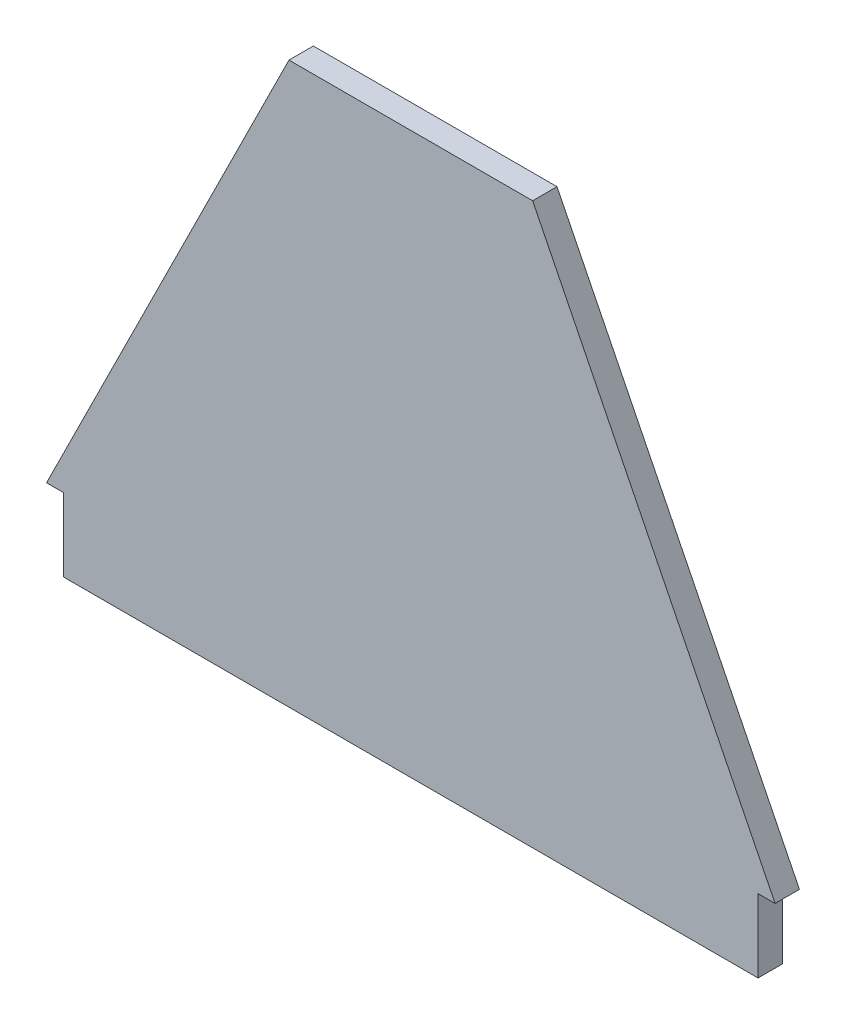
SolidWorks part; units mm, degrees
material "Balsa"
ref_plane "Front Plane" through (0, 0, 0) normal (0, 0, 1) x (1, 0, 0)
ref_plane "Top Plane" through (0, 0, 0) normal (0, 1, 0) x (1, 0, 0)
ref_plane "Right Plane" through (0, 0, 0) normal (1, 0, 0) x (0, 0, -1)
sketch "Sketch1" plane through (0, 0, 0) normal (0, 0, 1) x (1, 0, 0)
  line L0 (74.75, 15) -> (71.25, 15)
  line L5 (71.25, 15) -> (71.25, 0)
  line L6 (71.25, 0) -> (-71.25, 0)
  line L7 (-71.25, 0) -> (-71.25, 15)
  line L8 (-71.25, 15) -> (-74.75, 15)
  line L10 (0, 0) -> (0, 115) construction
  line L11 (-74.75, 15) -> (-25, 115)
  line L12 (74.75, 15) -> (25, 115)
  line L13 (-25, 115) -> (25, 115)
  point P3 (0, 0)
  point P4 (0, 0)
  point P10 (0, 115)
  point P12 (0, 115)
  dimension "D1" = 50
  dimension "D2" = 100
  dimension "D3" = 3.5
  dimension "D4" = 3.5
  dimension "D5" = 142.5
  dimension "D6" = 15
extrude "Boss-Extrude1" add sketch "Sketch1" along normal blind 5
